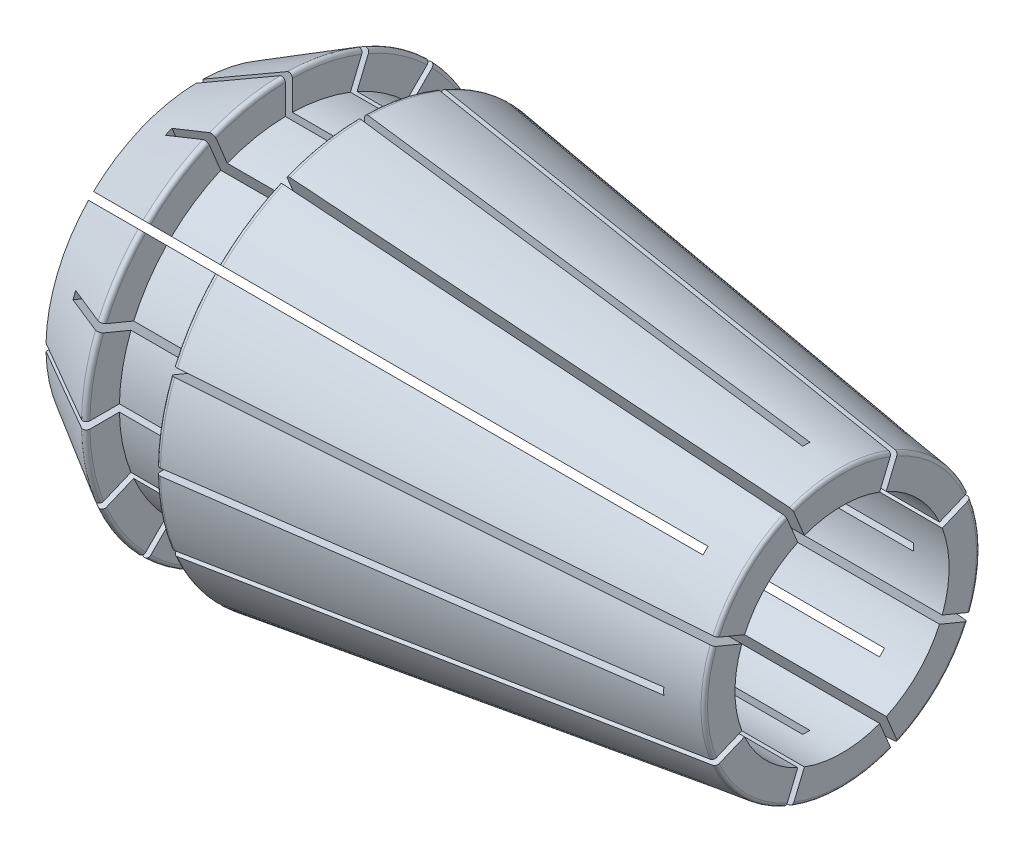
SolidWorks part; units mm, degrees
ref_plane "Front Plane" through (0, 0, 0) normal (0, 0, 1) x (1, 0, 0)
ref_plane "Top Plane" through (0, 0, 0) normal (0, 1, 0) x (1, 0, 0)
ref_plane "Right Plane" through (0, 0, 0) normal (1, 0, 0) x (0, 0, -1)
sketch "Sketch2" plane through (0, 0, 0) normal (1, 0, 0) x (0, 0, -1)
  circle A0 centre (0, 0) radius 5.75
  dimension "D1" = 11.5
extrude "Boss-Extrude1" add sketch "Sketch2" along normal blind 18
sketch "Sketch3" plane through (0, 0, 0) normal (0, 0, 1) x (1, 0, 0)
  line L0 (0, 0) -> (132.04, 0) construction
  line L1 (0, 4.3066) -> (2.5, 5.75)
  line L2 (0, 5.75) -> (0, -5.75) construction
  line L4 (2.5, 5.75) -> (2.5, 4.75)
  line L5 (2.5, 4.75) -> (4.5212, 4.75)
  line L6 (4.5212, 4.75) -> (4.5212, 5.75)
  line L7 (4.5212, 5.75) -> (18, 3.8557)
  line L8 (18, -5.75) -> (18, 5.75) construction
  line L9 (18, 3.8557) -> (18, 10.75)
  line L10 (18, 10.75) -> (0, 10.75)
  line L11 (0, 10.75) -> (0, 4.3066)
  line L13 (18, 5.75) -> (0, 5.75) construction
  line L15 (0, 0) -> (18, 0)
  line L16 (0, 0) -> (0, 3)
  line L17 (0, 3) -> (18, 3)
  line L18 (18, 0) -> (18, 3)
  point P9 (6.3, 5.5)
  dimension "D1" = 30
  dimension "D2" = 8
  dimension "D3" = 9.5
  dimension "D4" = 2.5
  dimension "D5" = 3.8
  dimension "D6" = 11
  dimension "D7" = 6
  dimension "D8" = 11.5
  dimension "D9" = 2.0212
  dimension "D10" = 5
revolve "Cut-Revolve1" cut sketch "Sketch3" angle 360 about L0
sketch "Sketch4" plane through (0, 0, 0) normal (-1, 0, 0) x (0, 0, 1)
  line L0 (21.8496, 21.991) -> (21.991, 21.8496)
  line L1 (-0.1, 31) -> (0.1, 31)
  line L2 (-0.1, 31) -> (-0.1, -31)
  line L3 (-0.1, -31) -> (0.1, -31)
  line L4 (0.1, 31) -> (0.1, -31)
  line L5 (-0.1, 31) -> (0.1, -31) construction
  line L6 (-0.1, -31) -> (0.1, 31) construction
  line L7 (21.8496, 21.991) -> (-21.991, -21.8496)
  line L8 (-21.991, -21.8496) -> (-21.8496, -21.991)
  line L9 (21.991, 21.8496) -> (-21.8496, -21.991)
  line L10 (21.8496, 21.991) -> (-21.8496, -21.991) construction
  line L11 (-21.991, -21.8496) -> (21.991, 21.8496) construction
  line L12 (31, 0.1) -> (31, -0.1)
  line L13 (31, 0.1) -> (-31, 0.1)
  line L14 (-31, 0.1) -> (-31, -0.1)
  line L15 (31, -0.1) -> (-31, -0.1)
  line L16 (31, 0.1) -> (-31, -0.1) construction
  line L17 (-31, 0.1) -> (31, -0.1) construction
  line L18 (21.991, -21.8496) -> (21.8496, -21.991)
  line L19 (21.991, -21.8496) -> (-21.8496, 21.991)
  line L20 (-21.8496, 21.991) -> (-21.991, 21.8496)
  line L21 (21.8496, -21.991) -> (-21.991, 21.8496)
  line L22 (21.991, -21.8496) -> (-21.991, 21.8496) construction
  line L23 (-21.8496, 21.991) -> (21.8496, -21.991) construction
  line L24 (0.1, -31) -> (-0.1, -31)
  line L25 (0.1, -31) -> (0.1, 31)
  line L26 (0.1, 31) -> (-0.1, 31)
  line L27 (-0.1, -31) -> (-0.1, 31)
  line L28 (0.1, -31) -> (-0.1, 31) construction
  line L29 (0.1, 31) -> (-0.1, -31) construction
  line L30 (-21.8496, -21.991) -> (-21.991, -21.8496)
  line L31 (-21.8496, -21.991) -> (21.991, 21.8496)
  line L32 (21.991, 21.8496) -> (21.8496, 21.991)
  line L33 (-21.991, -21.8496) -> (21.8496, 21.991)
  line L34 (-21.8496, -21.991) -> (21.8496, 21.991) construction
  line L35 (21.991, 21.8496) -> (-21.991, -21.8496) construction
  line L36 (-31, -0.1) -> (-31, 0.1)
  line L37 (-31, -0.1) -> (31, -0.1)
  line L38 (31, -0.1) -> (31, 0.1)
  line L39 (-31, 0.1) -> (31, 0.1)
  line L40 (-31, -0.1) -> (31, 0.1) construction
  line L41 (31, -0.1) -> (-31, 0.1) construction
  line L42 (-21.991, 21.8496) -> (-21.8496, 21.991)
  line L43 (-21.991, 21.8496) -> (21.8496, -21.991)
  line L44 (21.8496, -21.991) -> (21.991, -21.8496)
  line L45 (-21.8496, 21.991) -> (21.991, -21.8496)
  line L46 (-21.991, 21.8496) -> (21.991, -21.8496) construction
  line L47 (21.8496, -21.991) -> (-21.8496, 21.991) construction
  point P0 (0, 0)
  point P37 (0, 0)
  dimension "D3" = 31
  dimension "D1" = 0.2
  dimension "D2" = 8
extrude "Cut-Extrude1" cut sketch "Sketch4" against normal offset from surface (17 mm away) 1 contours L19 L20 L21 L18 | L13 L14 L15 L12 | L7 L8 L9 L0 | L4 L3 L2 L1 up to face at (18, 0, 3)
sketch "Sketch5" plane through (18, 0, 0) normal (1, 0, 0) x (0, 0, -1)
  line L0 (0, 0) -> (0, -5.7107) construction
  line L1 (-11.9556, -28.602) -> (-11.7708, -28.6785)
  line L2 (-11.9556, -28.602) -> (11.7708, 28.6785)
  line L3 (11.7708, 28.6785) -> (11.9556, 28.602)
  line L4 (-11.7708, -28.6785) -> (11.9556, 28.602)
  line L5 (-11.9556, -28.602) -> (11.9556, 28.602) construction
  line L6 (11.7708, 28.6785) -> (-11.7708, -28.6785) construction
  line L7 (28.602, 11.9556) -> (28.6785, 11.7708)
  line L8 (-28.602, -11.9556) -> (28.6785, 11.7708)
  line L9 (-28.6785, -11.7708) -> (28.602, 11.9556)
  line L10 (-28.6785, -11.7708) -> (-28.602, -11.9556)
  line L11 (28.6785, -11.7708) -> (28.602, -11.9556)
  line L12 (-28.6785, 11.7708) -> (28.602, -11.9556)
  line L13 (-28.602, 11.9556) -> (28.6785, -11.7708)
  line L14 (-28.602, 11.9556) -> (-28.6785, 11.7708)
  line L15 (11.9556, -28.602) -> (11.7708, -28.6785)
  line L16 (-11.9556, 28.602) -> (11.7708, -28.6785)
  line L17 (-11.7708, 28.6785) -> (11.9556, -28.602)
  line L18 (-11.7708, 28.6785) -> (-11.9556, 28.602)
  line L19 (-11.7708, -28.6785) -> (-11.9556, -28.602)
  line L20 (11.7708, 28.6785) -> (-11.9556, -28.602)
  line L21 (11.9556, 28.602) -> (-11.7708, -28.6785)
  line L22 (11.9556, 28.602) -> (11.7708, 28.6785)
  line L23 (-28.602, -11.9556) -> (-28.6785, -11.7708)
  line L24 (28.602, 11.9556) -> (-28.6785, -11.7708)
  line L25 (28.6785, 11.7708) -> (-28.602, -11.9556)
  line L26 (28.6785, 11.7708) -> (28.602, 11.9556)
  line L27 (-28.6785, 11.7708) -> (-28.602, 11.9556)
  line L28 (28.6785, -11.7708) -> (-28.602, 11.9556)
  line L29 (28.602, -11.9556) -> (-28.6785, 11.7708)
  line L30 (28.602, -11.9556) -> (28.6785, -11.7708)
  line L31 (-11.9556, 28.602) -> (-11.7708, 28.6785)
  line L32 (11.9556, -28.602) -> (-11.7708, 28.6785)
  line L33 (11.7708, -28.6785) -> (-11.9556, 28.602)
  line L34 (11.7708, -28.6785) -> (11.9556, -28.602)
  point P0 (0, 0)
  point P40 (0, 0)
  dimension "D1" = 0.2
  dimension "D2" = 22.5
  dimension "D3" = 8
extrude "Cut-Extrude2" cut sketch "Sketch5" against normal offset from surface (17 mm away) 1 contours L8 L7 L9 L10 | L12 L11 L13 L14 | L16 L15 L17 L18 | L4 L3 L2 L1 up to face at (0, 3.2638, 1.3519)
chamfer "Фаска1" distance 0.1 angle 60 8 edges at (0, -1.1481, -2.7716) (0, -2.7716, -1.1481) (0, -2.7716, 1.1481) (0, -1.1481, 2.7716) (0, 1.1481, 2.7716) (0, 2.7716, 1.1481) (0, 2.7716, -1.1481) (0, 1.1481, -2.7716)
fillet "Скругление1" radius 0.1 40 edges at (18, -2.7264, -2.7264) (18, 0, -3.8557) (18, 2.7264, -2.7264) (18, 3.8557, 0) (18, -3.8557, 0) (18, -2.7264, 2.7264) (18, 0, 3.8557) (18, 2.7264, 2.7264) (4.5212, 1.1218, -5.6395) (4.5212, 3.1945, -4.781) (4.5212, 4.781, -3.1945) (2.5, 4.781, -3.1945) (2.5, 3.1945, -4.781) (2.5, 1.1218, -5.6395) (4.5212, -4.781, -3.1945) (4.5212, -3.1945, -4.781) (4.5212, -1.1218, -5.6395) (2.5, -1.1218, -5.6395) (2.5, -3.1945, -4.781) (2.5, -4.781, -3.1945) (4.5212, -5.6395, -1.1218) (2.5, -5.6395, -1.1218) (2.5, -5.6395, 1.1218) (4.5212, -5.6395, 1.1218) (2.5, -4.781, 3.1945) (2.5, -3.1945, 4.781) (2.5, -1.1218, 5.6395) (4.5212, -4.781, 3.1945) (4.5212, -3.1945, 4.781) (4.5212, -1.1218, 5.6395) (4.5212, 1.1218, 5.6395) (2.5, 5.6395, -1.1218) (4.5212, 5.6395, -1.1218) (4.5212, 5.6395, 1.1218) (2.5, 5.6395, 1.1218) (2.5, 4.781, 3.1945) (2.5, 1.1218, 5.6395) (2.5, 3.1945, 4.781) (4.5212, 4.781, 3.1945) (4.5212, 3.1945, 4.781)
equation "\"L\"= 13.5"
